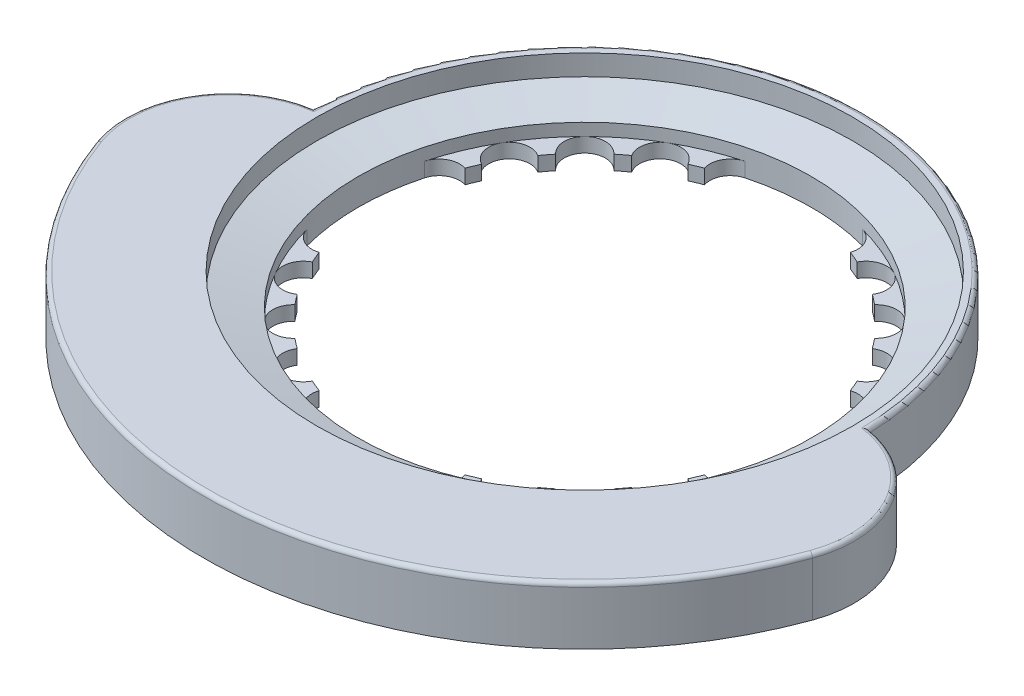
SolidWorks part; units mm, degrees
ref_plane "前视基准面" through (0, 0, 0) normal (0, 0, 1) x (1, 0, 0)
ref_plane "上视基准面" through (0, 0, 0) normal (0, 1, 0) x (1, 0, 0)
ref_plane "右视基准面" through (0, 0, 0) normal (1, 0, 0) x (0, 0, -1)
sketch "草图1" plane through (0, 0, 0) normal (0, 1, 0) x (1, 0, 0)
  circle A0 centre (0, 0) radius 13.5
  dimension "D1" = 27
extrude "凸台-拉伸1" add sketch "草图1" along normal blind 2.8
sketch "草图2" plane through (0, 2.8, 0) normal (0, 1, 0) x (1, 0, 0)
  circle A0 centre (0, 0) radius 13
  dimension "D1" = 26
extrude "切除-拉伸1" cut sketch "草图2" against normal blind 1
sketch "草图4" plane through (0, 0, 0) normal (0, 0, 1) x (1, 0, 0)
  line L0 (0, 0) -> (0, 1.3) construction
  line L1 (0, 1.3) -> (-11, 1.3)
  line L2 (-11, 1.3) -> (-13, 1.8)
  line L3 (-13, 1.8) -> (0, 1.8)
  line L4 (0, 1.8) -> (0, 1.3)
  dimension "D1" = 1.3
  dimension "D2" = 0.5
  dimension "D3" = 11
  dimension "D4" = 13
revolve "切除-旋转1" cut sketch "草图4" angle 360 about L4
sketch "草图5" plane through (0, 1.3, 0) normal (0, 1, 0) x (1, 0, 0)
  circle A1 centre (0, 0) radius 11
  circle A2 centre (0, 0) radius 11
  dimension "D1" = 0
extrude "切除-拉伸2" cut sketch "草图5" against normal blind 0.6
sketch "草图6" plane through (0, 0.7, 0) normal (0, 1, 0) x (1, 0, 0)
  arc A0 (-3.54, 9.3525) -> (-4.1101, 9.1163) centre (0, 0) ccw
  arc A1 (2.847, 10.6252) -> (-2.847, 10.6252) centre (0, 0) ccw
  arc A2 (3.54, 9.3525) -> (2.847, 10.6252) centre (2.5882, 9.6593) ccw
  arc A3 (5.8399, 8.1176) -> (4.1101, 9.1163) centre (5, 8.6603) ccw
  arc A4 (7.7419, 6.3295) -> (6.3295, 7.7419) centre (7.0711, 7.0711) ccw
  arc A5 (9.1163, 4.1101) -> (8.1176, 5.8399) centre (8.6603, 5) ccw
  arc A6 (10.6252, 2.847) -> (9.3525, 3.54) centre (9.6593, 2.5882) ccw
  arc A7 (9.3525, 3.54) -> (9.1163, 4.1101) centre (0, 0) ccw
  arc A8 (9.3525, -3.54) -> (10.6252, -2.847) centre (9.6593, -2.5882) ccw
  arc A9 (8.1176, -5.8399) -> (9.1163, -4.1101) centre (8.6603, -5) ccw
  arc A10 (6.3295, -7.7419) -> (7.7419, -6.3295) centre (7.0711, -7.0711) ccw
  arc A11 (4.1101, -9.1163) -> (5.8399, -8.1176) centre (5, -8.6603) ccw
  arc A12 (2.847, -10.6252) -> (3.54, -9.3525) centre (2.5882, -9.6593) ccw
  arc A13 (3.54, -9.3525) -> (4.1101, -9.1163) centre (0, 0) ccw
  arc A14 (-3.54, -9.3525) -> (-2.847, -10.6252) centre (-2.5882, -9.6593) ccw
  arc A15 (-5.8399, -8.1176) -> (-4.1101, -9.1163) centre (-5, -8.6603) ccw
  arc A16 (-7.7419, -6.3295) -> (-6.3295, -7.7419) centre (-7.0711, -7.0711) ccw
  arc A17 (-9.1163, -4.1101) -> (-8.1176, -5.8399) centre (-8.6603, -5) ccw
  arc A18 (-10.6252, -2.847) -> (-9.3525, -3.54) centre (-9.6593, -2.5882) ccw
  arc A19 (-9.3525, -3.54) -> (-9.1163, -4.1101) centre (0, 0) ccw
  arc A20 (-9.3525, 3.54) -> (-10.6252, 2.847) centre (-9.6593, 2.5882) ccw
  arc A21 (-8.1176, 5.8399) -> (-9.1163, 4.1101) centre (-8.6603, 5) ccw
  arc A22 (-6.3295, 7.7419) -> (-7.7419, 6.3295) centre (-7.0711, 7.0711) ccw
  arc A23 (-4.1101, 9.1163) -> (-5.8399, 8.1176) centre (-5, 8.6603) ccw
  arc A24 (-2.847, 10.6252) -> (-3.54, 9.3525) centre (-2.5882, 9.6593) ccw
  arc A25 (-5.8399, 8.1176) -> (-6.3295, 7.7419) centre (0, 0) ccw
  arc A26 (-7.7419, 6.3295) -> (-8.1176, 5.8399) centre (0, 0) ccw
  arc A27 (-9.1163, 4.1101) -> (-9.3525, 3.54) centre (0, 0) ccw
  arc A28 (4.1101, 9.1163) -> (3.54, 9.3525) centre (0, 0) ccw
  arc A29 (6.3295, 7.7419) -> (5.8399, 8.1176) centre (0, 0) ccw
  arc A30 (8.1176, 5.8399) -> (7.7419, 6.3295) centre (0, 0) ccw
  arc A31 (-10.6252, 2.847) -> (-10.6252, -2.847) centre (0, 0) ccw
  arc A32 (-8.1176, -5.8399) -> (-7.7419, -6.3295) centre (0, 0) ccw
  arc A33 (-6.3295, -7.7419) -> (-5.8399, -8.1176) centre (0, 0) ccw
  arc A34 (-4.1101, -9.1163) -> (-3.54, -9.3525) centre (0, 0) ccw
  arc A35 (5.8399, -8.1176) -> (6.3295, -7.7419) centre (0, 0) ccw
  arc A36 (7.7419, -6.3295) -> (8.1176, -5.8399) centre (0, 0) ccw
  arc A37 (9.1163, -4.1101) -> (9.3525, -3.54) centre (0, 0) ccw
  arc A38 (10.6252, -2.847) -> (10.6252, 2.847) centre (0, 0) ccw
  arc A39 (-2.847, -10.6252) -> (2.847, -10.6252) centre (0, 0) ccw
  point P78 (0, 0)
  dimension "D1" = 20
extrude "切除-拉伸3" cut sketch "草图6" against normal blind 0.7
sketch "草图7" plane through (0, 0, 0) normal (0, 1, 0) x (1, 0, 0)
  line L0 (0, 0) -> (0, -18.5) construction
  line L1 (0, 0) -> (-17.3843, -6.3274) construction
  line L2 (0, 0) -> (17.3843, -6.3274) construction
  line L3 (-17.3843, -6.3274) -> (-12.6859, -4.6173) construction
  line L4 (17.3843, -6.3274) -> (12.6859, -4.6173) construction
  arc A0 (-17.3843, -6.3274) -> (17.3843, -6.3274) centre (0, 0) ccw
  arc A1 (-13.4963, 0.3166) -> (13.4963, 0.3166) centre (0, 0) ccw
  arc A2 (-13.4963, 0.3166) -> (-17.3843, -6.3274) centre (-12.6859, -4.6173) ccw
  arc A3 (17.3843, -6.3274) -> (13.4963, 0.3166) centre (12.6859, -4.6173) ccw
  dimension "D1" = 37
  dimension "D4" = 27
  dimension "D2" = 70
  dimension "D3" = 70
extrude "凸台-拉伸2" add sketch "草图7" along normal blind 2.8
fillet "圆角1" radius 0.2 4 edges at (-17.0012, 2.8, 2.0919) (17.0012, 2.8, 2.0919) (0, 2.8, -13.5) (0, 2.8, 18.5)
